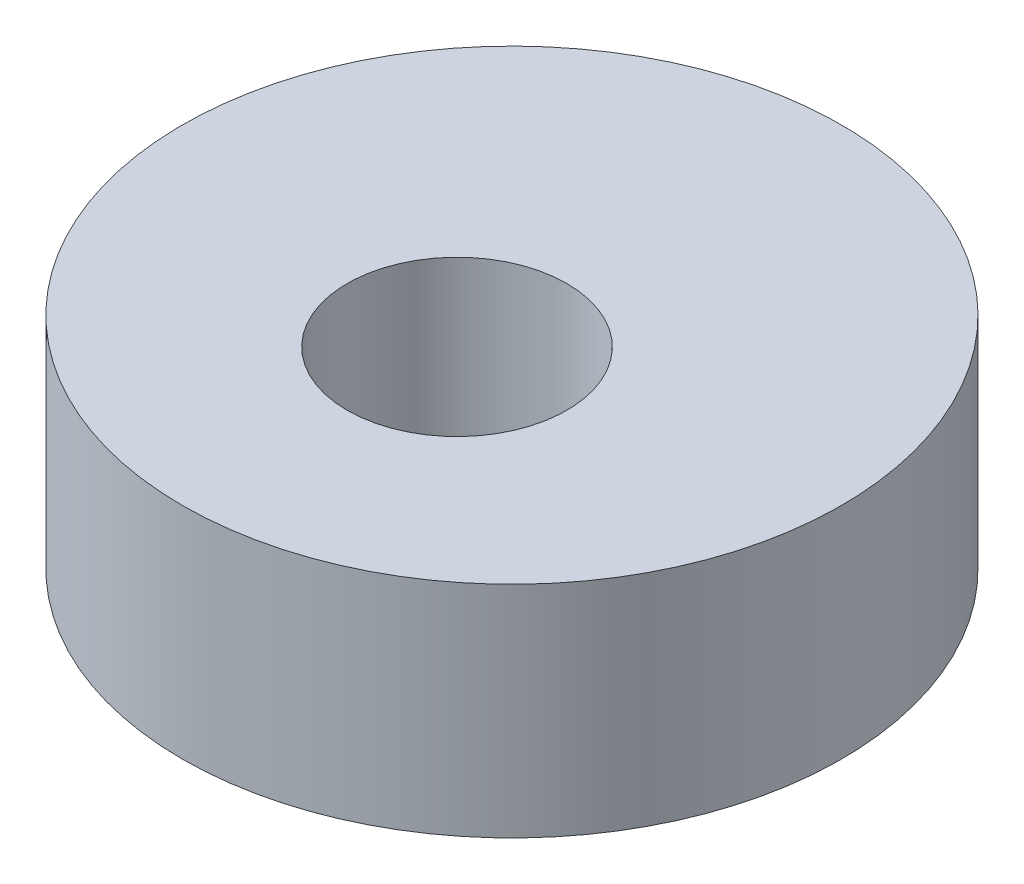
SolidWorks part; units mm, degrees
ref_plane "Front Plane" through (0, 0, 0) normal (0, 0, 1) x (1, 0, 0)
ref_plane "Top Plane" through (0, 0, 0) normal (0, 1, 0) x (1, 0, 0)
ref_plane "Right Plane" through (0, 0, 0) normal (1, 0, 0) x (0, 0, -1)
sketch "Sketch1" plane through (0, 0, 0) normal (0, 1, 0) x (1, 0, 0)
  line L0 (0, -1.5875) -> (0, 0) construction
  circle A0 centre (0, 0) radius 9.525
  circle A1 centre (0, -1.5875) radius 3.175
  dimension "D1" = 19.05
  dimension "D2" = 6.35
  dimension "D3" = 1.5875
extrude "Boss-Extrude1" add sketch "Sketch1" along normal blind 6.35
equation "\"R\"= 1.5in'radius of rotor"
equation "\"E\"= .125in'eccentricity"
equation "\"R_r\"= .125in'radius of roller"
equation "\"N\"= 14'number of rollers"
equation "\"R_o\"= .2in'output disk pin diameter"
equation "\"D3@Sketch1\"=\"E\"/2"
